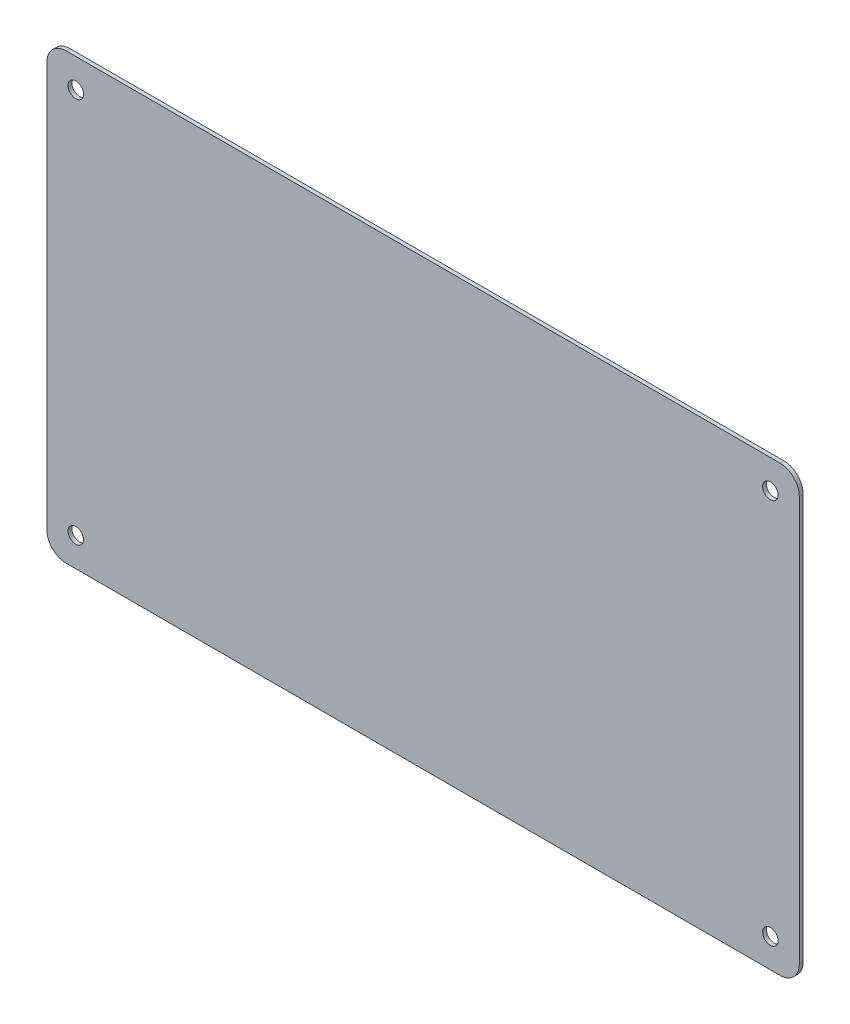
SolidWorks part; units mm, degrees
ref_plane "Спереди" through (0, 0, 0) normal (0, 0, 1) x (1, 0, 0)
ref_plane "Сверху" through (0, 0, 0) normal (0, 1, 0) x (1, 0, 0)
ref_plane "Справа" through (0, 0, 0) normal (1, 0, 0) x (0, 0, -1)
sketch "Эскиз1" plane through (0, 0, 0) normal (0, 0, 1) x (1, 0, 0)
  line L1 (-37, 23) -> (37, 23)
  line L2 (-39, 21) -> (-39, -21)
  line L3 (-37, -23) -> (37, -23)
  line L4 (39, 21) -> (39, -21)
  line L5 (-39, 23) -> (39, -23) construction
  line L6 (-39, -23) -> (39, 23) construction
  arc A0 (-37, 23) -> (-39, 21) centre (-37, 21) ccw
  arc A1 (-39, -21) -> (-37, -23) centre (-37, -21) ccw
  arc A2 (37, -23) -> (39, -21) centre (37, -21) ccw
  arc A3 (37, 23) -> (39, 21) centre (37, 21) cw
  point P0 (0, 0)
  dimension "D3" = 2
  dimension "D1" = 78
  dimension "D2" = 46
extrude "Бобышка-Вытянуть1" add sketch "Эскиз1" along normal blind 0.4
sketch "Эскиз2" plane through (0, 0, 0.4) normal (0, 0, 1) x (1, 0, 0)
  line L1 (-36, 20) -> (36, 20) construction
  line L2 (-36, 20) -> (-36, -20) construction
  line L3 (-36, -20) -> (36, -20) construction
  line L4 (36, 20) -> (36, -20) construction
  line L5 (-36, 20) -> (36, -20) construction
  line L6 (-36, -20) -> (36, 20) construction
  circle A0 centre (-36, 20) radius 0.8
  circle A1 centre (36, 20) radius 0.8
  circle A2 centre (36, -20) radius 0.8
  circle A3 centre (-36, -20) radius 0.8
  point P0 (0, 0)
  dimension "D3" = 1.6
  dimension "D1" = 72
  dimension "D2" = 40
extrude "Вырез-Вытянуть1" cut sketch "Эскиз2" against normal blind 1
